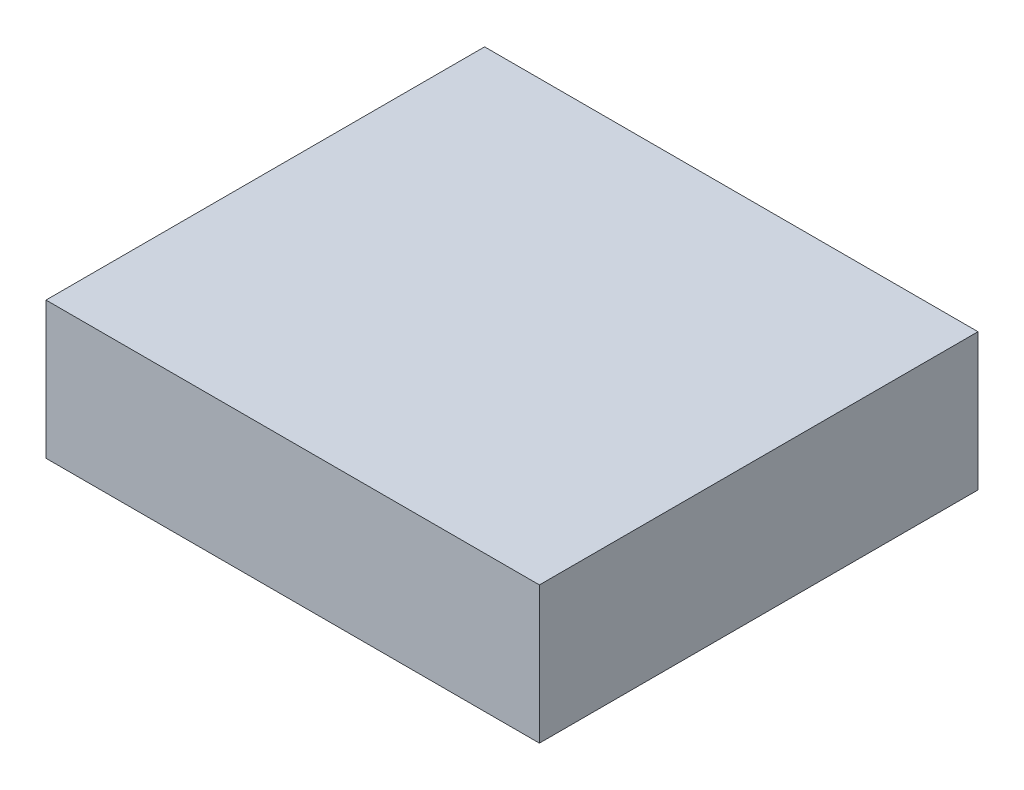
SolidWorks part; units mm, degrees
ref_plane "Front Plane" through (0, 0, 0) normal (0, 0, 1) x (1, 0, 0)
ref_plane "Top Plane" through (0, 0, 0) normal (0, 1, 0) x (1, 0, 0)
ref_plane "Right Plane" through (0, 0, 0) normal (1, 0, 0) x (0, 0, -1)
sketch "Sketch1" plane through (0, 0, 0) normal (0, 1, 0) x (1, 0, 0)
  line L1 (-9, 8) -> (9, 8)
  line L2 (-9, 8) -> (-9, -8)
  line L3 (-9, -8) -> (9, -8)
  line L4 (9, 8) -> (9, -8)
  line L5 (-9, 8) -> (9, -8) construction
  line L6 (-9, -8) -> (9, 8) construction
  point P0 (0, 0)
  dimension "D1" = 18
  dimension "D2" = 16
extrude "Boss-Extrude1" add sketch "Sketch1" along normal blind 5
